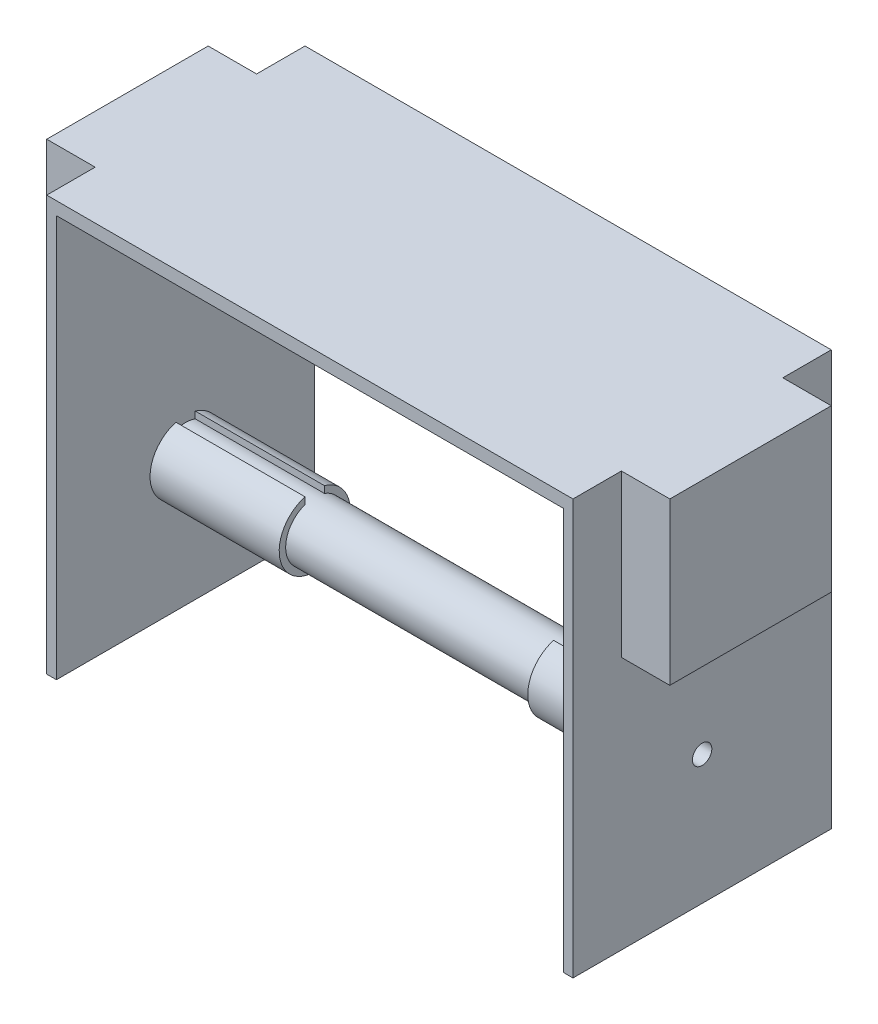
SolidWorks part; units mm, degrees
ref_plane "Alzado" through (0, 0, 0) normal (0, 0, 1) x (1, 0, 0)
ref_plane "Planta" through (0, 0, 0) normal (0, 1, 0) x (1, 0, 0)
ref_plane "Vista lateral" through (0, 0, 0) normal (1, 0, 0) x (0, 0, -1)
sketch "Croquis1" plane through (0, 0, 0) normal (1, 0, 0) x (0, 0, -1)
  line L1 (0, 12) -> (3, 12)
  line L2 (0, 12) -> (-3, 12)
  line L3 (-3, 12) -> (-3, 8.4853)
  line L4 (3, 12) -> (3, 8.4853)
  line L6 (-40, -40) -> (40, -40)
  line L7 (-40, -40) -> (-40, 40)
  line L9 (40, -40) -> (40, 40)
  line L12 (-3, 8.4853) -> (3, 8.4853)
  line L13 (-40, 8.4853) -> (-40, 88.4853)
  line L14 (-40, 88.4853) -> (40, 88.4853)
  line L15 (40, 8.4853) -> (40, 88.4853)
  arc A0 (-3, 8.4853) -> (3, 8.4853) centre (0, 0) ccw
  dimension "D1" = 18
  dimension "D3" = 3
  dimension "D4" = 3
  dimension "D5" = 80
  dimension "D6" = 80
  dimension "D7" = 80
extrude "Saliente-Extruir1" add sketch "Croquis1" along normal blind 3 from offset 80 contours L9 L15 L14 L13 L7 L6 A0 L3 L2 L1 L4
sketch "Croquis2" plane through (80, 0, 0) normal (-1, 0, 0) x (0, 0, 1)
  line L0 (3, 8.4853) -> (3, 10.583)
  line L3 (-3, 10.583) -> (-3, 8.4853)
  arc A0 (-3, 8.4853) -> (3, 8.4853) centre (0, 0) ccw
  arc A1 (-3, 10.583) -> (3, 10.583) centre (0, 0) ccw
  dimension "D1" = 22
extrude "Saliente-Extruir2" add sketch "Croquis2" along normal blind 40
sketch "Croquis3" plane through (0, 0, 0) normal (1, 0, 0) x (0, 0, -1)
  line L1 (40, 88.4853) -> (-40, 88.4853)
  line L2 (40, 88.4853) -> (40, -40)
  line L3 (40, -40) -> (-40, -40)
  line L4 (-40, 88.4853) -> (-40, -40)
extrude "Saliente-Extruir3" add sketch "Croquis3" along normal blind 3 from offset 80 separate body offset against normal yes
sketch "Croquis4" plane through (-77, 0, 0) normal (1, 0, 0) x (0, 0, -1)
  line L2 (-3, 10.583) -> (-3, 8.4853)
  line L3 (3, 10.583) -> (3, 8.4853)
  arc A0 (-3, 8.4853) -> (3, 8.4853) centre (0, 0) ccw
  arc A1 (-3, 10.583) -> (3, 10.583) centre (0, 0) ccw
  point P9 (0, 11)
  dimension "D1" = 22
extrude "Saliente-Extruir4" add sketch "Croquis4" along normal blind 40
sketch "Croquis5" plane through (0, 0, 0) normal (0, 1, 0) x (1, 0, 0)
  line L1 (-80, 40) -> (83, 40)
  line L2 (-80, 40) -> (-80, -40)
  line L3 (-80, -40) -> (83, -40)
  line L4 (83, 40) -> (83, -40)
extrude "Saliente-Extruir5" add sketch "Croquis5" along normal blind 4 from offset 84.5
sketch "Croquis6" plane through (83, 0, 0) normal (1, 0, 0) x (0, 0, -1)
  line L0 (3, 12) -> (3, 8.4853)
  line L1 (3, 12) -> (-3, 12)
  line L2 (-3, 12) -> (-3, 8.4853)
  arc A0 (-3, 8.4853) -> (3, 8.4853) centre (0, 0) ccw
extrude "Saliente-Extruir6" add sketch "Croquis6" against normal blind 3
sketch "Croquis7" plane through (0, 0, 0) normal (0, 1, 0) x (1, 0, 0)
  line L0 (-80, 25) -> (-80, -25)
  line L1 (-80, 40) -> (-80, -40) construction
  line L2 (83, 25) -> (83, -25)
  line L3 (83, -40) -> (83, 40) construction
  line L4 (-95, -25) -> (-95, 25)
  line L5 (98, -25) -> (98, 25)
  line L6 (-95, 25) -> (-80, 25)
  line L7 (98, 25) -> (83, 25)
  line L8 (-95, -25) -> (-80, -25)
  line L9 (98, -25) -> (83, -25)
  point P12 (-95, 0)
  point P15 (98, 0)
  dimension "D3" = 50
  dimension "D4" = 50
extrude "Saliente-Extruir7" add sketch "Croquis7" against normal blind 50 from offset 88.5
sketch "Croquis8" plane through (-77, 0, 0) normal (1, 0, 0) x (0, 0, -1)
  circle A0 centre (0, 0) radius 9
  dimension "D1" = 18
extrude "Saliente-Extruir8" add sketch "Croquis8" along normal up to surface (157 mm away) up to face at (80, -0.2329, 0)
sketch "Croquis10" plane through (-80, 0, 0) normal (-1, 0, 0) x (0, 0, 1)
  line L0 (0, -3) -> (0, -40)
  line L2 (40, -40) -> (-40, -40) construction
  circle A1 centre (0, 0) radius 3
  dimension "D3" = 6
  dimension "D1" = 37
extrude "Cortar-Extruir1" cut sketch "Croquis10" against normal blind 20 contours A1
sketch "Croquis11" plane through (83, 0, 0) normal (1, 0, 0) x (0, 0, -1)
  line L0 (0, -40) -> (0, -3)
  line L1 (-40, -40) -> (40, -40) construction
  circle A0 centre (0, 0) radius 3
  dimension "D2" = 6
  dimension "D1" = 37
extrude "Cortar-Extruir2" cut sketch "Croquis11" against normal blind 20 contours A0
